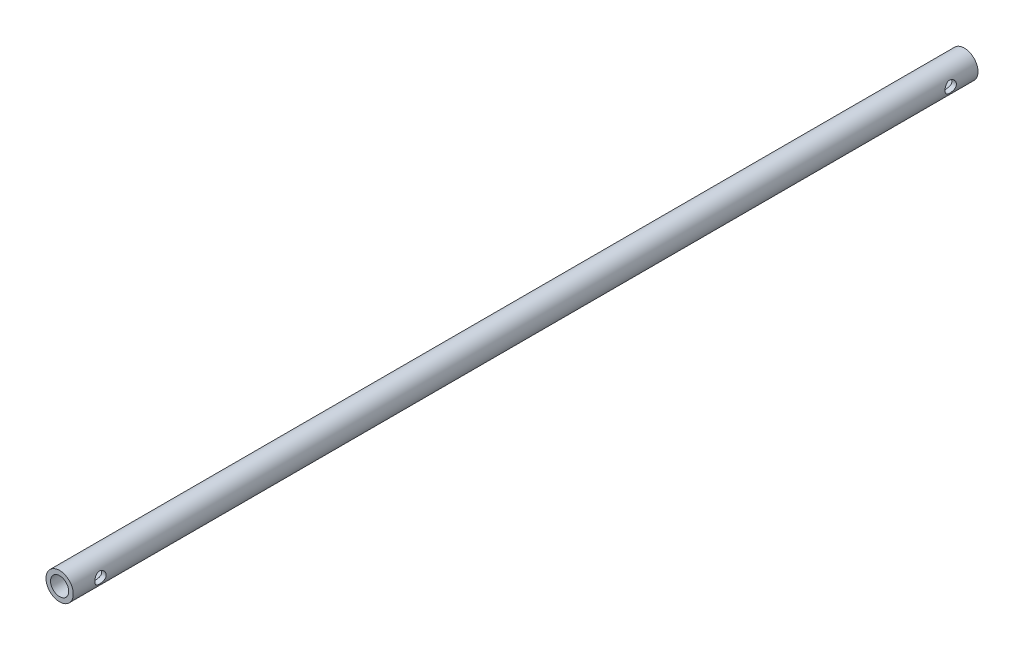
SolidWorks part; units mm, degrees
ref_plane "Front" through (0, 0, 0) normal (0, 0, 1) x (1, 0, 0)
ref_plane "Top" through (0, 0, 0) normal (0, 1, 0) x (1, 0, 0)
ref_plane "Right" through (0, 0, 0) normal (1, 0, 0) x (0, 0, -1)
sketch "Esquisse1" plane through (0, 0, 0) normal (0, 0, 1) x (1, 0, 0)
  circle A0 centre (0, 0) radius 2
  circle A1 centre (0, 0) radius 3
  dimension "D1" = 6
  dimension "D2" = 4
extrude "Boss.-Extru.1" add sketch "Esquisse1" along normal blind 199
sketch "Esquisse2" plane through (0, 0, 0) normal (1, 0, 0) x (0, 0, -1)
  line L0 (0, -3) -> (0, 3) construction
  line L1 (-199, 3) -> (-199, -3) construction
  circle A0 centre (-6, 0) radius 1.25
  circle A1 centre (-193, 0) radius 1.25
  dimension "D1" = 2.5
  dimension "D2" = 6
  dimension "D3" = 6
extrude "Enlèv. mat.-Extru.1" cut sketch "Esquisse2" against normal through all both and the other way through all
